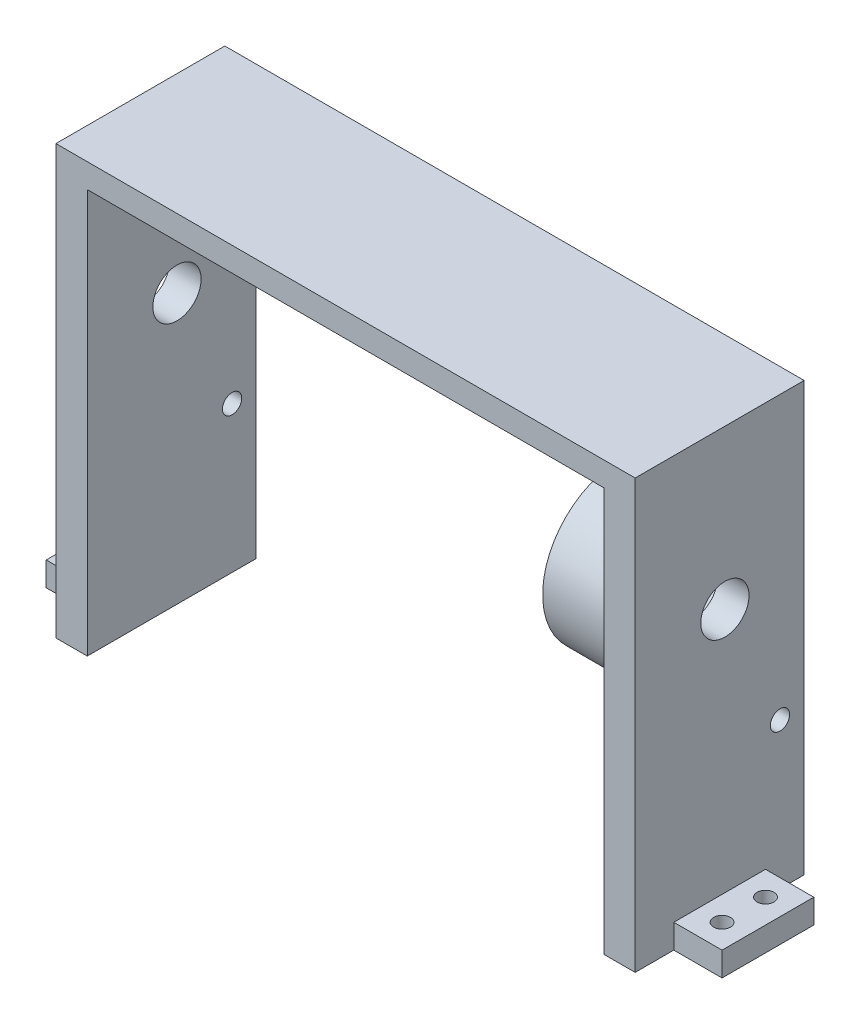
SolidWorks part; units mm, degrees
ref_plane "Plan de face" through (0, 0, 0) normal (0, 0, 1) x (1, 0, 0)
ref_plane "Plan de dessus" through (0, 0, 0) normal (0, 1, 0) x (1, 0, 0)
ref_plane "Plan de droite" through (0, 0, 0) normal (1, 0, 0) x (0, 0, -1)
sketch "Esquisse4" plane through (0, 0, 0) normal (1, 0, 0) x (0, 0, -1)
  line L0 (35, -37.6041) -> (30, -37.6041)
  line L1 (35, 51.0959) -> (0, 51.0959)
  line L2 (35, 51.0959) -> (35, -37.6041)
  line L3 (35, -37.6041) -> (0, -37.6041)
  line L4 (0, 51.0959) -> (0, -37.6041)
  circle A0 centre (30, -7.3141) radius 2
  circle A1 centre (18.5858, 18.2537) radius 5
  point P8 (17.5, -37.6041)
  point P9 (30, -17.6212)
  point P10 (30, -7.3141)
  point P11 (30, -17.6212)
  point P12 (30, -17.6331)
  point P13 (18.5858, 18.2537)
  dimension "D4" = 4
  dimension "D6" = 10
  dimension "D1" = 35
  dimension "D2" = 88.7
  dimension "D3" = 28
  dimension "D7" = 30.29
extrude "Boss.-Extru.1" add sketch "Esquisse4" along normal blind 120 contours L1 L4 L3 L0 L2 A1 A0
sketch "Esquisse18" plane through (0, 0, 0) normal (-1, 0, 0) x (0, 0, 1)
  circle A0 centre (-18.5858, 18.2537) radius 13.75
  circle A1 centre (-18.5858, 18.2537) radius 16.25
  dimension "D1" = 27.5
  dimension "D2" = 32.5
sketch "Esquisse19" plane through (0, 0, -35) normal (0, 0, -1) x (-1, 0, 0)
  line L0 (-120, -37.6041) -> (0, -37.6041) construction
  line L1 (-113.5, -37.6041) -> (-6.5, -37.6041)
  line L2 (-113.5, -37.6041) -> (-113.5, 46.0959)
  line L3 (-113.5, 46.0959) -> (-6.5, 46.0959)
  line L4 (-6.5, -37.6041) -> (-6.5, 46.0959)
  line L5 (-120, 51.0959) -> (-120, -37.6041) construction
  line L6 (0, 2.0037) -> (0, 34.5037) construction
  line L7 (-120, 51.0959) -> (0, 51.0959) construction
  dimension "D1" = 6.5
  dimension "D2" = 6.5
  dimension "D3" = 5
extrude "Enlèv. mat.-Extru.1" cut sketch "Esquisse19" against normal blind 120
sketch "Esquisse20" plane through (120, 0, 0) normal (1, 0, 0) x (0, 0, -1)
  circle A0 centre (18.5858, 18.2537) radius 14
  circle A1 centre (18.5858, 18.2537) radius 16.25
  dimension "D1" = 28
extrude "Boss.-Extru.2" add sketch "Esquisse20" against normal blind 21.5
sketch "Esquisse28" plane through (120, 0, 0) normal (1, 0, 0) x (0, 0, -1)
  line L0 (35, -37.6041) -> (0, -37.6041) construction
  line L1 (8, -37.6041) -> (27, -37.6041)
  line L2 (8, -37.6041) -> (8, -32.6041)
  line L3 (8, -32.6041) -> (27, -32.6041)
  line L4 (27, -37.6041) -> (27, -32.6041)
  line L5 (0, 51.0959) -> (0, -37.6041) construction
  line L6 (35, 51.0959) -> (35, -37.6041) construction
  point P8 (27, -35.1041)
  dimension "D1" = 8
  dimension "D2" = 8
  dimension "D3" = 5
extrude "Boss.-Extru.6" add sketch "Esquisse28" along normal blind 10
sketch "Esquisse29" plane through (0, -32.6041, 0) normal (0, 1, 0) x (1, 0, 0)
  line L0 (130, 27) -> (120, 27) construction
  line L1 (130, 8) -> (120, 8) construction
  circle A0 centre (125, 22) radius 1.75
  circle A1 centre (125, 13) radius 1.75
  dimension "D1" = 3.5
  dimension "D2" = 3.5
  dimension "D3" = 5
  dimension "D4" = 5
extrude "Enlèv. mat.-Extru.6" cut sketch "Esquisse29" against normal blind 10
sketch "Esquisse33" plane through (0, 0, 0) normal (-1, 0, 0) x (0, 0, 1)
  line L0 (-35, -37.6041) -> (0, -37.6041) construction
  line L1 (-27, -37.6041) -> (-8, -37.6041)
  line L2 (-27, -37.6041) -> (-27, -32.6041)
  line L3 (-27, -32.6041) -> (-8, -32.6041)
  line L4 (-8, -37.6041) -> (-8, -32.6041)
  line L5 (-35, 51.0959) -> (-35, -37.6041) construction
  line L6 (0, 51.0959) -> (0, -37.6041) construction
  dimension "D1" = 8
  dimension "D2" = 8
  dimension "D3" = 5
extrude "Boss.-Extru.7" add sketch "Esquisse33" along normal blind 10
sketch "Esquisse34" plane through (0, -32.6041, 0) normal (0, 1, 0) x (1, 0, 0)
  line L0 (-10, 27) -> (0, 27) construction
  line L1 (-10, 8) -> (0, 8) construction
  circle A0 centre (-5, 22) radius 1.9751
  circle A1 centre (-5, 13) radius 2.1255
  dimension "D1" = 5
  dimension "D2" = 5
extrude "Enlèv. mat.-Extru.7" cut sketch "Esquisse34" against normal through all
sketch "Esquisse22" plane through (0, 0, 0) normal (-1, 0, 0) x (0, 0, 1)
  line L1 (0, -37.6041) -> (-20.5797, -37.6041)
  line L2 (0, -37.6041) -> (0, -32.6041)
  line L3 (0, -32.6041) -> (-20.5797, -32.6041)
  line L4 (-20.5797, -37.6041) -> (-20.5797, -32.6041)
  dimension "D1" = 5
sketch "Esquisse25" plane through (120, 0, 0) normal (1, 0, 0) x (0, 0, -1)
  line L0 (0, 51.0959) -> (0, -37.6041) construction
  line L1 (0, -37.6041) -> (35, -37.6041)
  line L2 (0, -37.6041) -> (0, -32.6041)
  line L3 (0, -32.6041) -> (35, -32.6041)
  line L4 (35, -37.6041) -> (35, -32.6041)
  line L5 (35, 51.0959) -> (35, -37.6041) construction
  dimension "D1" = 5
